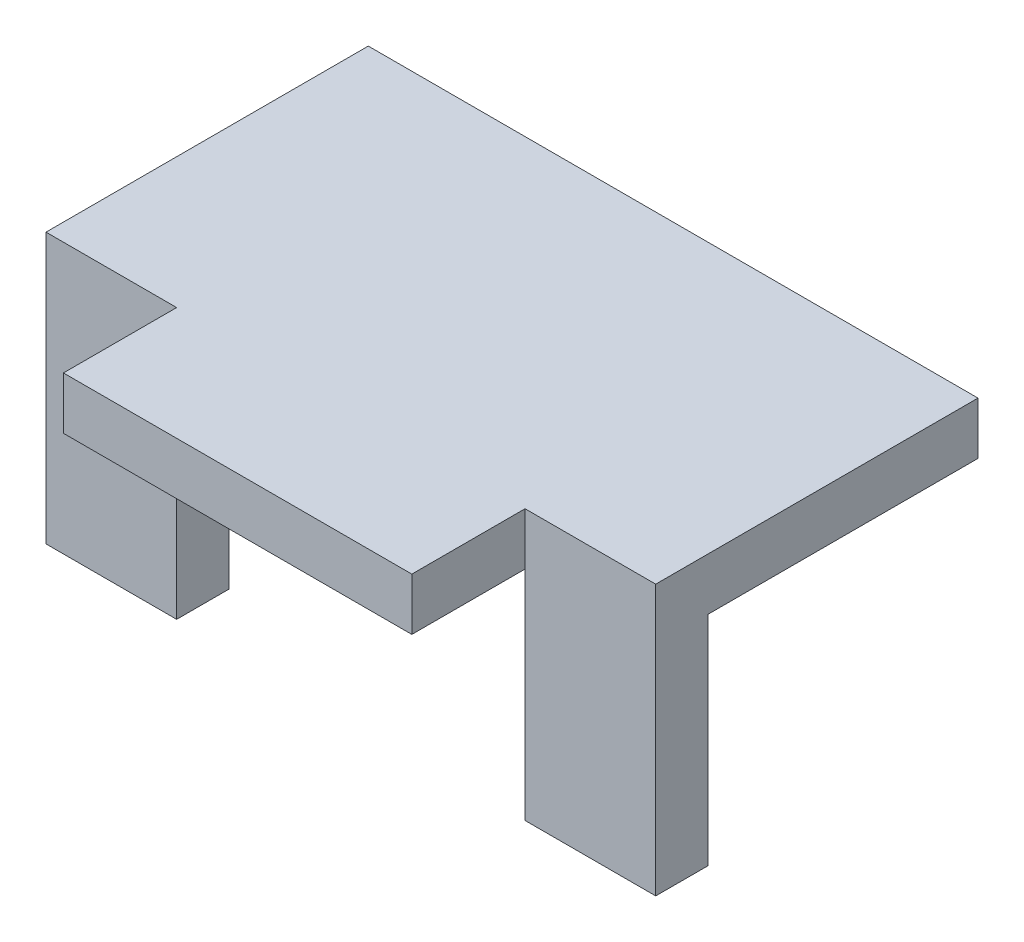
SolidWorks part; units mm, degrees
ref_plane "Front Plane" through (0, 0, 0) normal (0, 0, 1) x (1, 0, 0)
ref_plane "Top Plane" through (0, 0, 0) normal (0, 1, 0) x (1, 0, 0)
ref_plane "Right Plane" through (0, 0, 0) normal (1, 0, 0) x (0, 0, -1)
sketch "Sketch1" plane through (0, 0, 0) normal (0, 1, 0) x (1, 0, 0)
  line L1 (-35, -25) -> (35, -25)
  line L2 (-35, -25) -> (-35, 25)
  line L3 (-35, 25) -> (35, 25)
  line L4 (35, -25) -> (35, 25)
  line L5 (-35, -25) -> (35, 25) construction
  line L6 (-35, 25) -> (35, -25) construction
  point P1 (0, 0)
  dimension "D1" = 70
  dimension "D2" = 50
extrude "Boss-Extrude1" add sketch "Sketch1" along normal blind 6
sketch "Sketch2" plane through (0, 0, 0) normal (0, -1, 0) x (1, 0, 0)
  line L0 (-35, 12) -> (-20, 12)
  line L1 (-35, -25) -> (-35, 25) construction
  line L2 (-20, 12) -> (-20, 37.1745)
  line L3 (-20, 37.1745) -> (-39.6651, 37.1745)
  line L4 (-39.6651, 37.1745) -> (-39.6651, 12)
  line L5 (-39.6651, 12) -> (-35, 12)
  line L7 (-35, 25) -> (35, 25) construction
  line L8 (0, 45.4317) -> (0, -39.197) construction
  line L9 (39.6651, 12) -> (35, 12)
  line L10 (39.6651, 37.1745) -> (39.6651, 12)
  line L11 (20, 37.1745) -> (39.6651, 37.1745)
  line L12 (20, 12) -> (20, 37.1745)
  line L13 (35, 12) -> (20, 12)
  dimension "D1" = 15
  dimension "D2" = 13
extrude "Cut-Extrude1" cut sketch "Sketch2" against normal through all
sketch "Sketch3" plane through (0, 0, 0) normal (0, -1, 0) x (1, 0, 0)
  line L0 (-35, -25) -> (-35, 12) construction
  line L1 (-20, 12) -> (-35, 12)
  line L2 (-20, 12) -> (-20, 6)
  line L3 (-20, 6) -> (-35, 6)
  line L4 (-35, 12) -> (-35, 6)
  line L5 (35, 12) -> (35, -25) construction
  line L6 (20, 12) -> (35, 12)
  line L7 (20, 12) -> (20, 6)
  line L8 (20, 6) -> (35, 6)
  line L9 (35, 12) -> (35, 6)
  dimension "D1" = 6
  dimension "D2" = 6
extrude "Boss-Extrude2" add sketch "Sketch3" along normal blind 25
